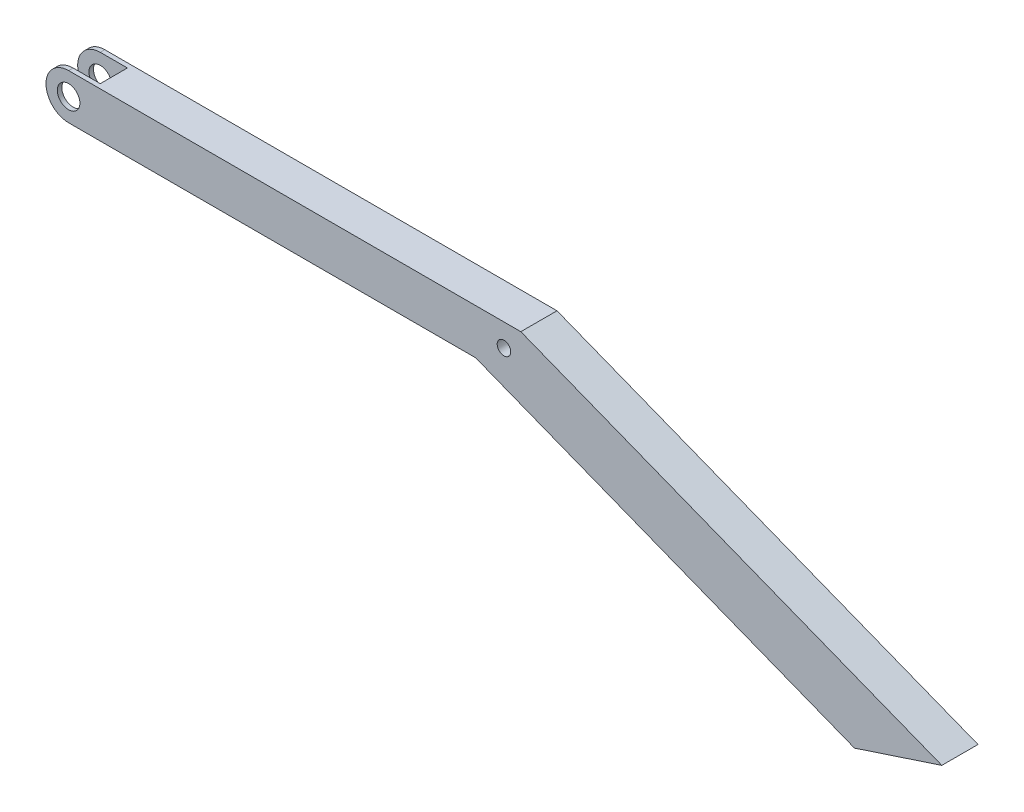
SolidWorks part; units mm, degrees
ref_plane "前视基准面" through (0, 0, 0) normal (0, 0, 1) x (1, 0, 0)
ref_plane "上视基准面" through (0, 0, 0) normal (0, 1, 0) x (1, 0, 0)
ref_plane "右视基准面" through (0, 0, 0) normal (1, 0, 0) x (0, 0, -1)
sketch "草图1" plane through (0, 0, 0) normal (0, 0, 1) x (1, 0, 0)
  line L0 (-83.2314, 14.5602) -> (-43.2314, 14.5602)
  line L1 (-83.2314, 4.5602) -> (-43.2314, 4.5602)
  line L2 (-43.2314, 14.5602) -> (16.7686, 14.5602)
  line L3 (-43.2314, 4.5602) -> (6.7686, 4.5602)
  line L4 (16.7686, 14.5602) -> (109.8651, -21.9508)
  line L5 (6.7686, 4.5602) -> (90.5554, -28.2997)
  line L6 (109.8651, -21.9508) -> (90.5554, -28.2997)
  arc A0 (-83.2314, 14.5602) -> (-83.2314, 4.5602) centre (-83.2314, 9.5602) ccw
  circle A2 centre (-83.2314, 9.5602) radius 2.5
  circle A3 centre (13.0411, 9.5602) radius 1.5
  dimension "D2" = 5
  dimension "D3" = 50
  dimension "D1" = 40
  dimension "D4" = 60
  dimension "D5" = 100
extrude "凸台-拉伸2" add sketch "草图1" along normal mid plane 8
sketch "草图2" plane through (0, 0, 0) normal (0, 0, 1) x (1, 0, 0)
  line L0 (-83.2314, 4.5602) -> (-77.2314, 4.5602)
  line L1 (-83.2314, 4.5602) -> (6.7686, 4.5602) construction
  line L2 (-83.2314, 14.5602) -> (-77.2314, 14.5602)
  line L3 (16.7686, 14.5602) -> (-83.2314, 14.5602) construction
  line L4 (-77.2314, 14.5602) -> (-77.2314, 4.5602)
  arc A0 (-83.2314, 14.5602) -> (-83.2314, 4.5602) centre (-83.2314, 9.5602) ccw
  dimension "D1" = 6
extrude "切除-拉伸1" cut sketch "草图2" against normal mid plane 6
